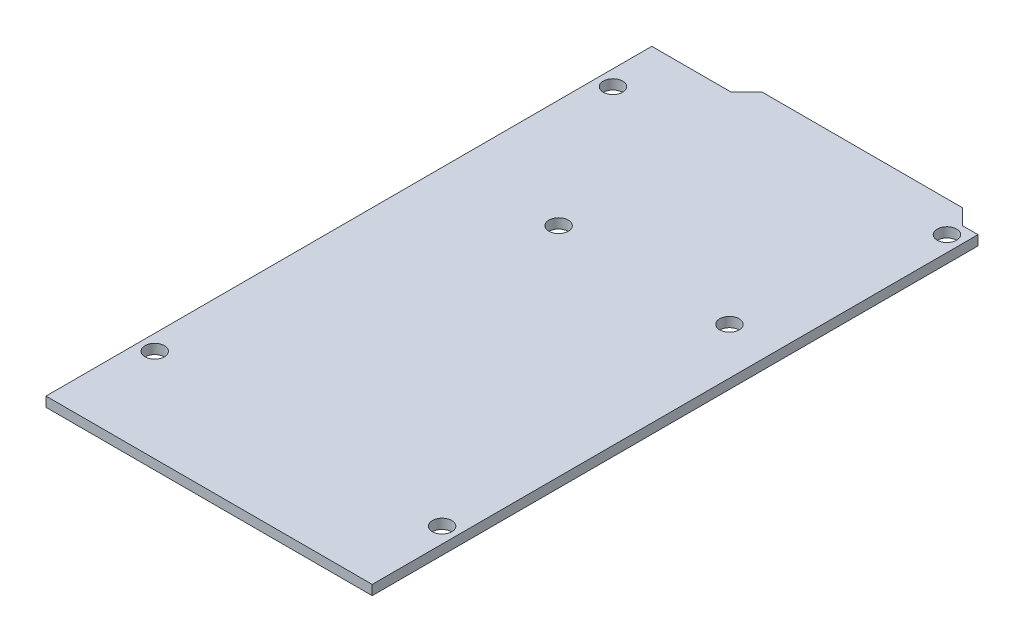
SolidWorks part; units mm, degrees
material "E-Glass Fiber"
ref_plane "Front Plane" through (0, 0, 0) normal (0, 0, 1) x (1, 0, 0)
ref_plane "Top Plane" through (0, 0, 0) normal (0, 1, 0) x (1, 0, 0)
ref_plane "Right Plane" through (0, 0, 0) normal (1, 0, 0) x (0, 0, -1)
sketch "Sketch1" plane through (0, 0, 0) normal (0, 1, 0) x (1, 0, 0)
  line L0 (-55, 0) -> (55, 0) construction
  line L1 (0, 0) -> (-53.34, 0)
  line L2 (0, 0) -> (0, 99.06)
  line L3 (-5.08, 101.6) -> (-37.846, 101.6)
  line L4 (-53.34, 0) -> (-53.34, 99.06)
  line L5 (-53.34, 99.06) -> (-40.386, 99.06)
  line L6 (-40.386, 99.06) -> (-37.846, 101.6)
  line L7 (-5.08, 101.6) -> (-2.54, 99.06)
  line L8 (-2.54, 99.06) -> (0, 99.06)
  circle A0 centre (-7.62, 66.04) radius 1.5875
  circle A1 centre (-35.56, 66.04) radius 1.5875
  circle A2 centre (-2.54, 13.97) radius 1.5875
  circle A3 centre (-50.8, 15.24) radius 1.5875
  circle A4 centre (-2.54, 96.52) radius 1.5875
  circle A5 centre (-50.8, 90.17) radius 1.5875
  dimension "D8" = 3.175
  dimension "D16" = 96.52
  dimension "D1" = 101.6
  dimension "D2" = 53.34
  dimension "D3" = 99.06
  dimension "D4" = 2.54
  dimension "D5" = 45
  dimension "D6" = 45
  dimension "D7" = 40.386
  dimension "D9" = 66.04
  dimension "D10" = 35.56
  dimension "D11" = 7.62
  dimension "D12" = 13.97
  dimension "D13" = 2.54
  dimension "D14" = 15.24
  dimension "D15" = 50.8
  dimension "D17" = 90.17
extrude "Boss-Extrude1" add sketch "Sketch1" against normal blind 1.6
sketch "Sketch2" plane through (0, 0, 0) normal (0, 1, 0) x (1, 0, 0)
  circle A0 centre (-50.8, 90.17) radius 1.5875
  circle A1 centre (-2.54, 96.52) radius 1.5875
  circle A2 centre (-7.62, 66.04) radius 1.5875
  circle A3 centre (-35.56, 66.04) radius 1.5875
  circle A4 centre (-2.54, 13.97) radius 1.5875
  circle A5 centre (-50.8, 15.24) radius 1.5875
